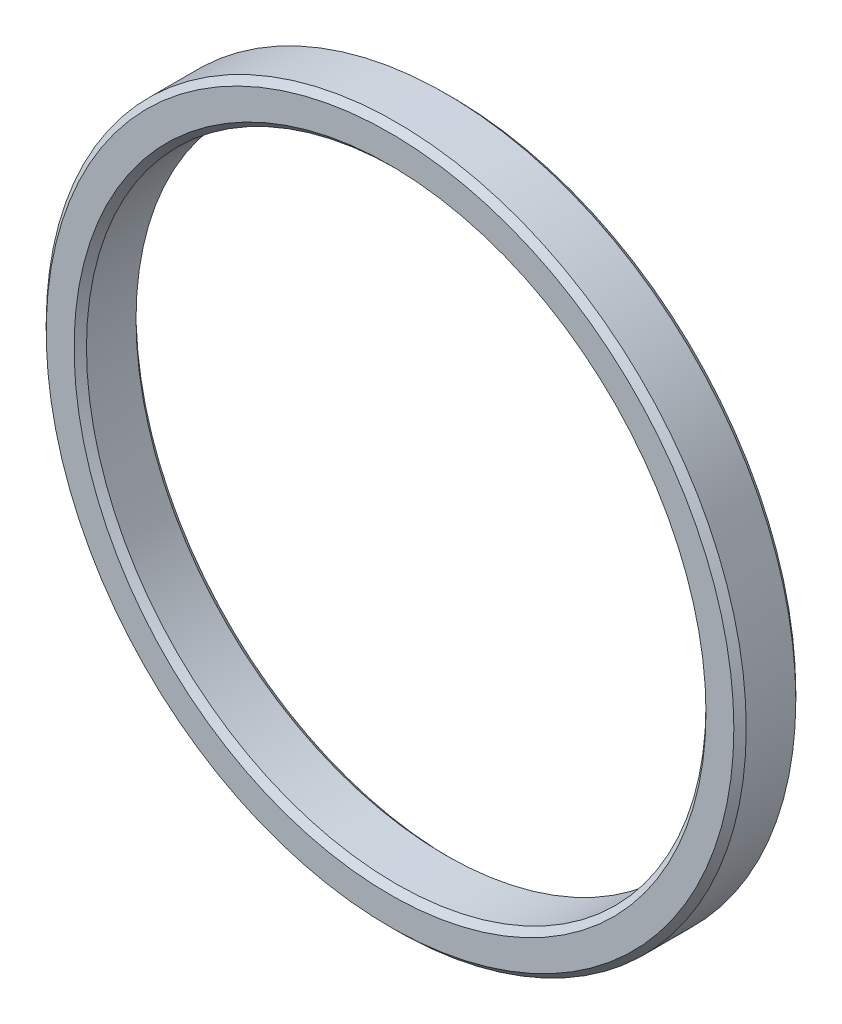
SolidWorks part; units mm, degrees
ref_plane "前视基准面" through (0, 0, 0) normal (0, 0, 1) x (1, 0, 0)
ref_plane "上视基准面" through (0, 0, 0) normal (0, 1, 0) x (1, 0, 0)
ref_plane "右视基准面" through (0, 0, 0) normal (1, 0, 0) x (0, 0, -1)
sketch "Sketch1" plane through (0, 0, 0) normal (0, 0, 1) x (1, 0, 0)
  circle A0 centre (0, 0) radius 113
  circle A1 centre (0, 0) radius 100
  dimension "D1" = 226
  dimension "D2" = 200
extrude "Extrude1" add sketch "Sketch1" along normal mid plane 20
chamfer "Chamfer1" distance 2 angle 45 4 edges at (100, 0, -10) (113, 0, -10) (100, 0, 10) (113, 0, 10)
